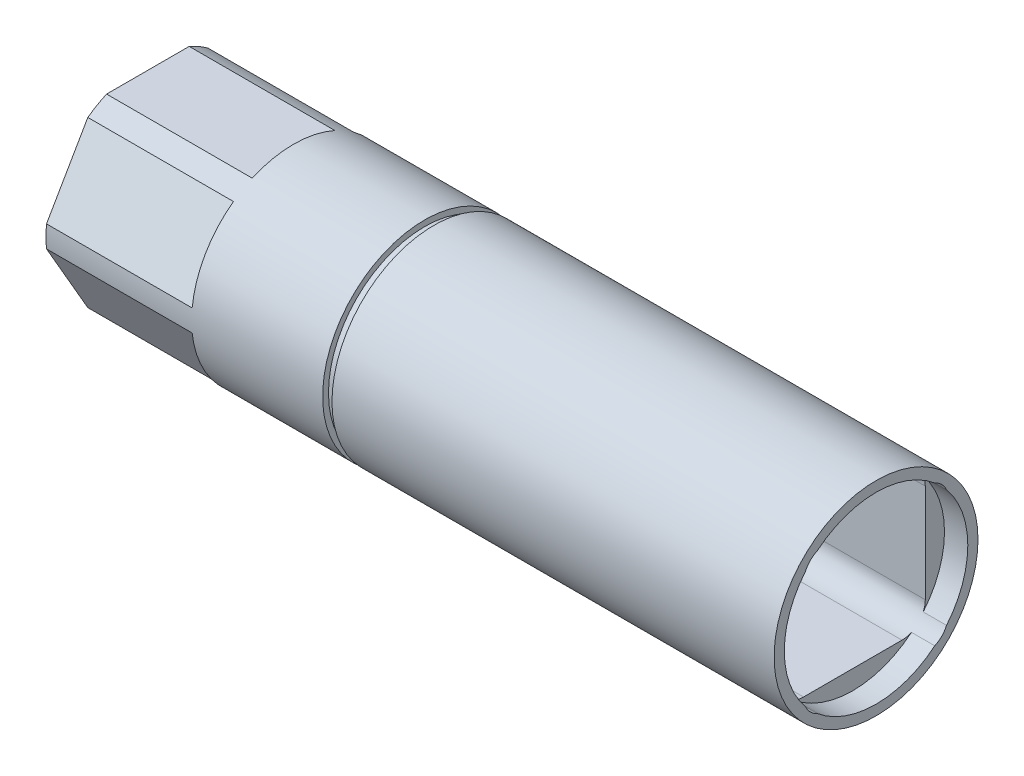
SolidWorks part; units mm, degrees
material "Plain Carbon Steel"
ref_plane "Front Plane" through (0, 0, 0) normal (0, 0, 1) x (1, 0, 0)
ref_plane "Top Plane" through (0, 0, 0) normal (0, 1, 0) x (1, 0, 0)
ref_plane "Right Plane" through (0, 0, 0) normal (1, 0, 0) x (0, 0, -1)
sketch "Sketch1" plane through (0, 0, 0) normal (0, 0, 1) x (1, 0, 0)
  line L0 (0, 0) -> (0, 17.5)
  line L1 (0, 17.5) -> (125, 17.5)
  line L2 (125, 17.5) -> (125, 0)
  line L3 (125, 0) -> (0, 0)
  line L4 (0, 0) -> (-29.537, 0) construction
  dimension "D1" = 35
  dimension "D2" = 125
revolve "Revolve1" add sketch "Sketch1" angle 360 about L4
sketch "Sketch3" plane through (125, 0, 0) normal (1, 0, 0) x (0, 0, -1)
  circle A0 centre (0, 0) radius 15.75
  dimension "D1" = 31.5
extrude "Cut-Extrude1" cut sketch "Sketch3" against normal blind 4
sketch "Sketch4" plane through (121, 0, 0) normal (1, 0, 0) x (0, 0, -1)
  line L0 (-8.45, 12.45) -> (8.45, 12.45)
  line L1 (-12.45, 8.45) -> (-12.45, -8.45)
  line L2 (12.45, 8.45) -> (12.45, -8.45)
  line L3 (-8.45, -12.45) -> (8.45, -12.45)
  line L4 (-12.45, 12.45) -> (12.45, -12.45) construction
  line L5 (12.45, 12.45) -> (-12.45, -12.45) construction
  arc A0 (-12.45, 8.45) -> (-8.45, 12.45) centre (-8.45, 8.45) cw
  arc A1 (-12.45, -8.45) -> (-8.45, -12.45) centre (-8.45, -8.45) ccw
  arc A2 (12.45, -8.45) -> (8.45, -12.45) centre (8.45, -8.45) cw
  arc A3 (8.45, 12.45) -> (12.45, 8.45) centre (8.45, 8.45) cw
  point P1 (0, 0)
  dimension "D1" = 4
  dimension "D2" = 24.9
extrude "Cut-Extrude2" cut sketch "Sketch4" against normal blind 25 and the other way blind 25
sketch "Sketch5" plane through (0, 0, 0) normal (-1, 0, 0) x (0, 0, 1)
  line L1 (9.2376, 16) -> (-9.2376, 16)
  line L2 (-9.2376, 16) -> (-18.4752, 0)
  line L3 (-18.4752, 0) -> (-9.2376, -16)
  line L4 (-9.2376, -16) -> (9.2376, -16)
  line L5 (9.2376, -16) -> (18.4752, 0)
  line L6 (18.4752, 0) -> (9.2376, 16)
  circle A0 centre (0, 0) radius 16 construction
  dimension "D1" = 32
extrude "Cut-Extrude3" cut sketch "Sketch5" against normal blind 25 flip side to cut
sketch "Sketch6" plane through (0, 0, 0) normal (0, 1, 0) x (1, 0, 0)
  line L0 (49.1, 29.467) -> (49.1, 16.5)
  line L1 (49.1, 29.467) -> (47.5, 29.467)
  line L2 (49.1, 16.5) -> (47.5, 16.5)
  line L3 (47.5, 29.467) -> (47.5, 16.5)
  line L4 (49.1, 29.467) -> (47.5, 16.5) construction
  line L5 (49.1, 16.5) -> (47.5, 29.467) construction
  line L6 (0, 0) -> (38.6469, 0) construction
  line L7 (25, 17.4008) -> (25, 10.312) construction
  point P1 (48.3, 22.9835)
  dimension "D1" = 33
  dimension "D2" = 1.6
  dimension "D3" = 22.5
revolve "Cut-Revolve1" cut sketch "Sketch6" angle 360 about L6
hole_wizard "M10x1.5 Tapped Hole1" positions "Sketch8" profile "Sketch7" tap size "M10x1.5" standard "BSI"
sketch "Sketch8" plane through (0, 0, 0) normal (-1, 0, 0) x (0, 0, 1)
  point P0 (0, 0)
sketch "Sketch7" plane through (0, 0, 0) normal (0, 1, 0) x (0, 0, 1)
  line L0 (0, 0) -> (0, 27.0537)
  line L1 (0, 27.0537) -> (4.25, 24.5)
  line L2 (4.25, 24.5) -> (4.25, 0)
  line L5 (4.25, 0) -> (0, 0)
  line L10 (0, 27.0537) -> (-4.25, 24.5) construction
  line L11 (0, -6.35) -> (0, 107.95) construction
  dimension "Tap Drill Dia." = 8.5
  dimension "Tap Drill Depth" = 24.5
  dimension "Drill Angle" = 118
cosmetic thread "Hole Thread1" parameters "D1"=20, "D2"=10
